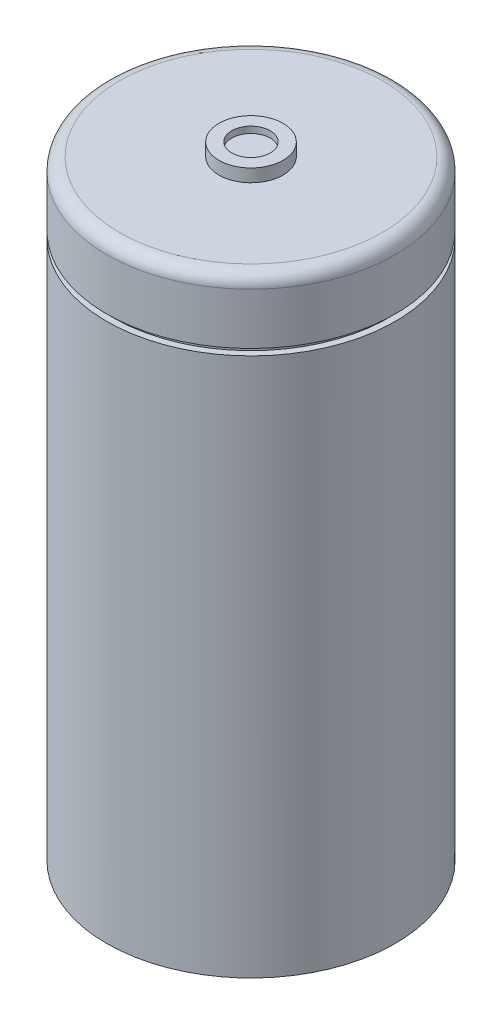
SolidWorks part; units mm, degrees
ref_plane "Спереди" through (0, 0, 0) normal (0, 0, 1) x (1, 0, 0)
ref_plane "Сверху" through (0, 0, 0) normal (0, 1, 0) x (1, 0, 0)
ref_plane "Справа" through (0, 0, 0) normal (1, 0, 0) x (0, 0, -1)
sketch "Эскиз1" plane through (0, 0, 0) normal (0, 1, 0) x (1, 0, 0)
  circle A0 centre (0, 0) radius 22.5
  dimension "D1" = 45
extrude "Бобышка-Вытянуть1" add sketch "Эскиз1" along normal blind 95
sketch "Эскиз2" plane through (0, 0, 0) normal (0, 0, 1) x (1, 0, 0)
  line L0 (0, 95) -> (0, 70.5593) construction
  line L1 (22.5, 95) -> (-22.5, 95) construction
  line L2 (21.5, 85) -> (22.5, 85)
  line L3 (22.5, 0) -> (22.5, 95) construction
  line L4 (22.5, 85) -> (22.5, 84)
  line L5 (22.5, 84) -> (21.5, 84)
  line L6 (21.5, 84) -> (21.5, 85)
revolve "Вырез-Повернуть1" cut sketch "Эскиз2" angle 360 about L0
fillet "Скругление1" radius 2 1 edges at (0, 95, 22.5)
sketch "Эскиз3" plane through (0, 95, 0) normal (0, 1, 0) x (1, 0, 0)
  circle A0 centre (0, 0) radius 5
  dimension "D1" = 10
extrude "Бобышка-Вытянуть2" add sketch "Эскиз3" along normal blind 2
sketch "Эскиз4" plane through (0, 97, 0) normal (0, 1, 0) x (1, 0, 0)
  circle A0 centre (0, 0) radius 3
  dimension "D1" = 6
extrude "Вырез-Вытянуть1" cut sketch "Эскиз4" against normal blind 1
